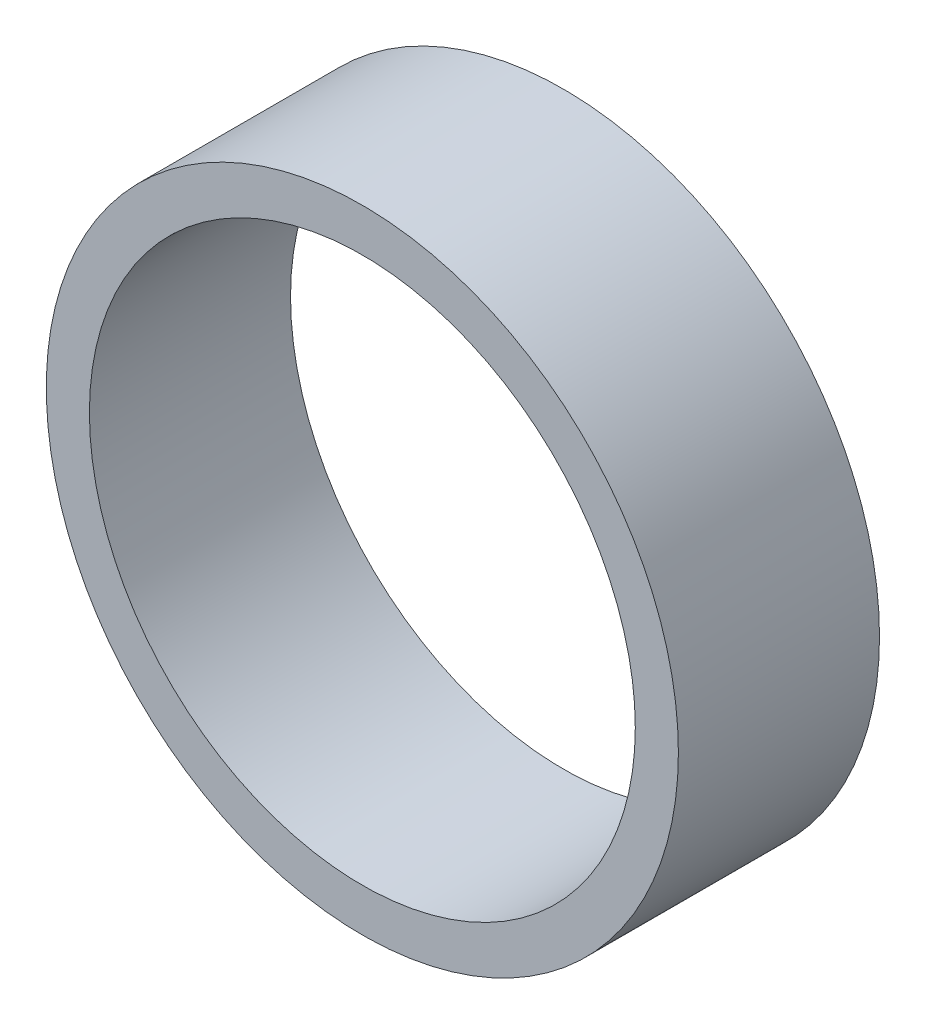
SolidWorks part; units mm, degrees
ref_plane "Alzado" through (0, 0, 0) normal (0, 0, 1) x (1, 0, 0)
ref_plane "Planta" through (0, 0, 0) normal (0, 1, 0) x (1, 0, 0)
ref_plane "Vista lateral" through (0, 0, 0) normal (1, 0, 0) x (0, 0, -1)
sketch "Croquis1" plane through (0, 0, 0) normal (0, 0, 1) x (1, 0, 0)
  circle A0 centre (0, 0) radius 9.5
  circle A1 centre (0, 0) radius 11
extrude "Saliente-Extruir1" add sketch "Croquis1" along normal blind 7
